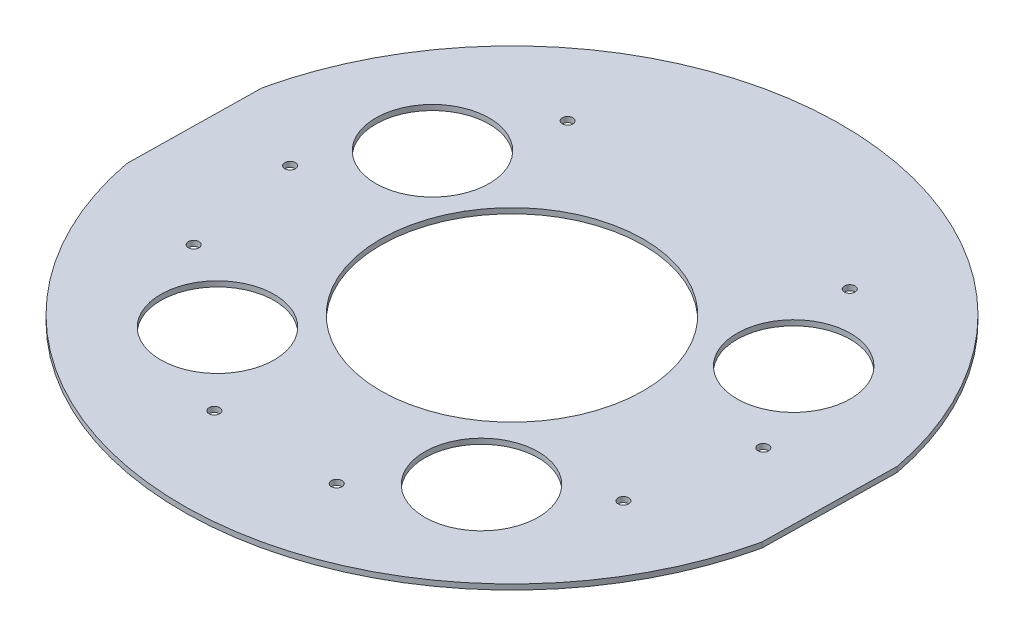
SolidWorks part; units mm, degrees
material "PTFE (general)"
ref_plane "Front Plane" through (0, 0, 0) normal (0, 0, 1) x (1, 0, 0)
ref_plane "Top Plane" through (0, 0, 0) normal (0, 1, 0) x (1, 0, 0)
ref_plane "Right Plane" through (0, 0, 0) normal (1, 0, 0) x (0, 0, -1)
sketch "Sketch1" plane through (0, 0, 0) normal (0, 1, 0) x (-0.9999, 0, 0.0151)
  line L2 (16.7097, 8.315) -> (15.9336, -16.6729)
  line L3 (-104.3119, 12.0739) -> (-105.088, -12.914)
  circle A0 centre (-44.1892, -2.2995) radius 24.651
  arc A1 (-105.088, -12.914) -> (15.9336, -16.6729) centre (-44.1892, -2.2995) ccw
  arc A2 (16.7097, 8.315) -> (-104.3119, 12.0739) centre (-44.1892, -2.2995) ccw
extrude "Boss-Extrude1" add sketch "Sketch1" along normal blind 1
ref_plane "Plane1" through (0.0585, 0, -3.6698) normal (0.016, 0, -0.9999) x (-0.9999, 0, -0.016)
ref_plane "Plane2" through (44.0909, 0, 0.7034) normal (-0.9999, 0, -0.016) x (-0.016, 0, 0.9999)
sketch "Sketch12" plane through (0, 1, 0) normal (0, 1, 0) x (1, 0, 0)
  circle A0 centre (68.8352, -27.4484) radius 10.65
  circle A1 centre (18.5061, -26.6455) radius 10.65
  circle A2 centre (10.0134, 22.1804) radius 10.65
  circle A3 centre (78.8809, 21.0818) radius 10.65
extrude "Cut-Extrude11" cut sketch "Sketch12" against normal blind 10
extrude "Cut-Extrude12" cut sketch "Sketch13" against normal blind 8 and the other way through all
sketch "Sketch13" plane through (48.228, 0, -7.72) normal (0, 1, 0) x (-0.9999, 0, -0.016)
  circle A0 centre (-13.0987, 51.8027) radius 1
  circle A1 centre (21.1033, 51.8027) radius 1
  circle A2 centre (40.6503, 18.1569) radius 1
  circle A3 centre (55.5443, -5.1203) radius 1
  circle A4 centre (20.5093, -31.747) radius 1
  circle A5 centre (-12.5047, -31.747) radius 1
  circle A6 centre (-47.5397, -5.1203) radius 1
  circle A7 centre (-32.6457, 18.1569) radius 1
extrude "Cut-Extrude15" cut sketch "Sketch16" against normal blind 10
sketch "Sketch16" plane through (48.228, 1, -7.72) normal (0, 1, 0) x (-0.9999, 0, -0.016)
  circle A0 centre (-13.0987, 51.8027) radius 1
  circle A1 centre (21.1033, 51.8027) radius 1
  circle A2 centre (40.6503, 18.1569) radius 1
  circle A3 centre (55.5443, -5.1203) radius 1
  circle A4 centre (20.5093, -31.747) radius 1
  circle A5 centre (-12.5047, -34.0973) radius 1
  circle A6 centre (-47.5397, -7.4705) radius 1
  circle A7 centre (-32.6457, 18.1569) radius 1
extrude "Cut-Extrude16" cut sketch "Sketch17" against normal blind 12
sketch "Sketch17" plane through (48.228, 1, -7.72) normal (0, 1, 0) x (-0.9999, 0, -0.016)
  circle A0 centre (-7.6628, 48.4869) radius 1
  circle A1 centre (15.6674, 48.4869) radius 1
  circle A2 centre (44.9674, 23.9204) radius 1
  circle A3 centre (49.1209, 2.1076) radius 1
  circle A4 centre (30.8998, -31.5077) radius 1
  circle A5 centre (-22.8952, -31.5077) radius 1
  circle A6 centre (-41.1164, 2.1076) radius 1
  circle A7 centre (-36.9628, 23.9204) radius 1
